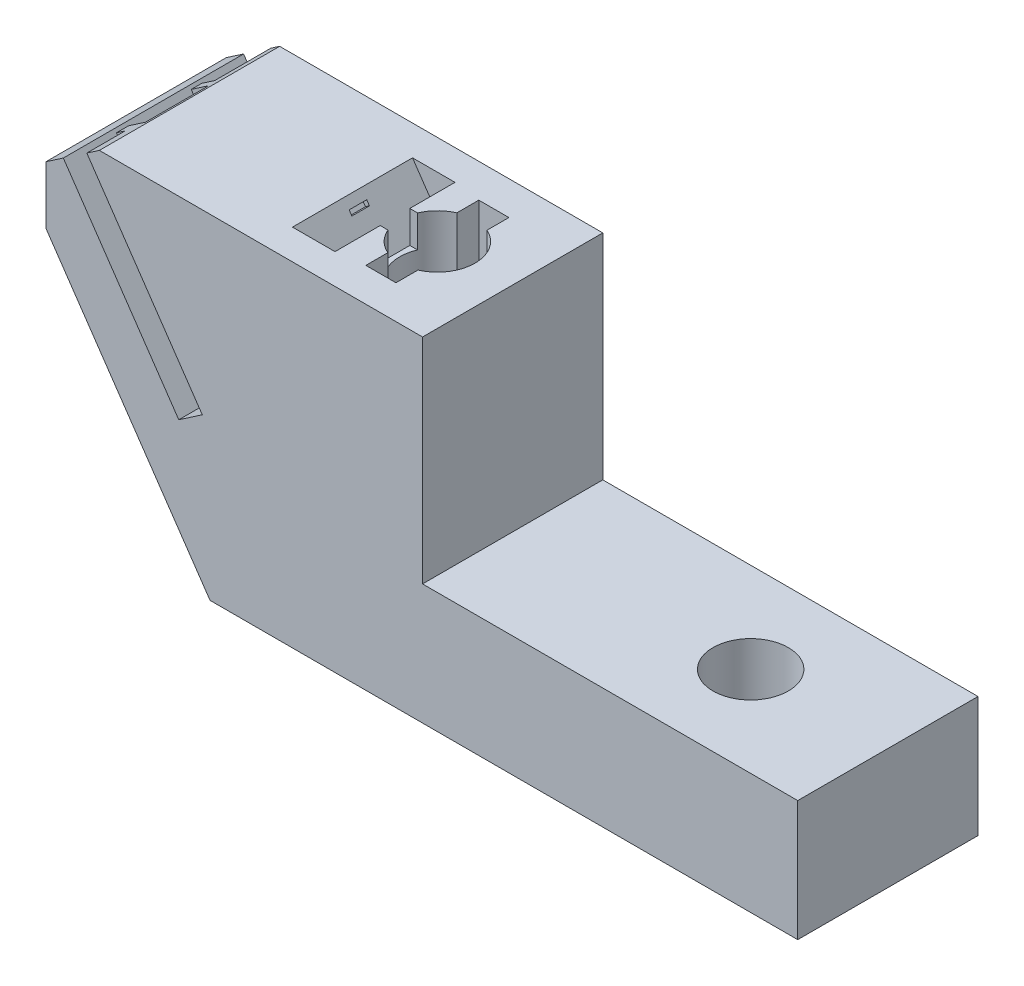
SolidWorks part; units mm, degrees
ref_plane "Front Plane" through (0, 0, 0) normal (0, 0, 1) x (1, 0, 0)
ref_plane "Top Plane" through (0, 0, 0) normal (0, 1, 0) x (1, 0, 0)
ref_plane "Right Plane" through (0, 0, 0) normal (1, 0, 0) x (0, 0, -1)
sketch "Sketch1" plane through (0, 0, 0) normal (0, 0, 1) x (1, 0, 0)
  line L6 (2.54, 23.749) -> (2.54, 14.224) construction
  line L7 (0, 0) -> (5.08, 0)
  line L8 (0, 0) -> (0, 14.224)
  line L9 (0, 14.224) -> (5.08, 14.224)
  line L14 (5.08, 0) -> (5.08, 14.224)
  line L19 (-4.6156, 24.384) -> (-4.0424, 23.5451)
  line L29 (-11.679, 6.821) -> (-21.27, 20.8572)
  line L31 (-22.86, -3.81) -> (8.89, -3.81)
  line L33 (-3.4692, 22.7063) -> (-1.0331, 19.1411)
  line L34 (-21.27, 20.8572) -> (-22.86, 19.7707)
  line L35 (-4.0424, 23.5451) -> (-3.4692, 22.7063)
  line L36 (-28.3165, 23.749) -> (25.4257, 23.749)
  line L37 (-28.3165, 23.749) -> (-28.3165, 38.989)
  line L38 (-28.3165, 38.989) -> (25.4257, 38.989)
  line L39 (25.4257, 23.749) -> (25.4257, 38.989)
  line L40 (2.54, 38.989) -> (2.54, 23.749) construction
  line L41 (2.54, 31.369) -> (-11.8891, 14.2184) construction
  line L42 (-21.27, 20.8572) -> (-17.9673, 23.1139)
  line L43 (-11.679, 6.821) -> (-8.3764, 9.0777)
  line L44 (-8.3764, 9.0777) -> (-9.5047, 10.729)
  line L45 (-1.0331, 19.1411) -> (0, 19.1411)
  line L46 (-17.9673, 23.1139) -> (-16.1085, 24.384)
  line L47 (-16.1085, 24.384) -> (-4.6156, 24.384)
  line L48 (0, 19.1411) -> (0, 14.224)
  line L49 (-4.329, 23.9646) -> (-17.443, 23.4721)
  line L50 (-4.329, 23.9646) -> (-3.7558, 23.1257)
  line L51 (-3.7558, 23.1257) -> (-8.3764, 9.0777)
  line L52 (-8.8063, 9.7068) -> (2.54, 42.6656) construction
  line L53 (2.54, 38.989) -> (2.54, 42.6656) construction
  line L54 (8.89, -3.81) -> (8.89, 24.384)
  line L55 (8.89, 24.384) -> (5.08, 24.384)
  line L56 (5.08, 14.224) -> (5.08, 24.384)
  line L57 (2.54, 23.749) -> (-4.0424, 23.5451) construction
  line L58 (2.54, 38.989) -> (-4.0424, 23.5451) construction
  line L59 (-4.0424, 23.5451) -> (-9.5047, 10.729) construction
  line L60 (-4.0424, 23.5451) -> (-17.9673, 23.1139) construction
  line L61 (-17.9673, 23.1139) -> (-9.5047, 10.729)
  line L62 (-8.8063, 9.7068) -> (-9.8549, 8.9903) construction
  line L63 (-9.8549, 8.9903) -> (-18.2379, 21.2588) construction
  line L64 (-18.2379, 21.2588) -> (-17.1893, 21.9753) construction
  line L69 (-17.1893, 21.9753) -> (2.54, 24.3311) construction
  line L70 (-22.86, 19.7707) -> (-22.86, -3.81)
  dimension "D1" = 5.08
  dimension "D2" = 14.224
  dimension "D3" = 0.635
  dimension "D4" = 10.16
  dimension "D5" = 4
  dimension "D6" = 15.24
  dimension "D7" = 17
  dimension "D8" = 31.75
  dimension "D9" = 1.59
  dimension "D10" = 1.016
  dimension "D11" = 6.35
  dimension "D12" = 3.81
  dimension "D13" = 3.81
  dimension "D14" = 0.635
  dimension "D15" = 0.508
  dimension "D16" = 0.508
  dimension "D17" = 0.762
  dimension "D18" = 14.859
  dimension "D19" = 1.27
  dimension "D20" = 15
extrude "Boss-Extrude1" add sketch "Sketch1" along normal blind 2.5 contours L34 L70 L31 L54 L36 L56 L14 L7 L8 L48 L45 L33 L35 L19 L46 L61 L44 L43 L29 | L47 L46 L36 L19 | L56 L36 L54 L55
sketch "Sketch2" plane through (0, 0, 2.5) normal (0, 0, 1) x (1, 0, 0)
  line L0 (-21.27, 20.8572) -> (-11.679, 6.821)
  line L1 (-21.27, 20.8572) -> (-18.0093, 23.0852)
  line L2 (-11.679, 6.821) -> (-8.4184, 9.049)
  line L3 (-18.0093, 23.0852) -> (-8.4184, 9.049)
  line L4 (-18.0093, 23.0852) -> (-16.1085, 24.384)
  line L5 (-16.1085, 24.384) -> (8.89, 24.384)
  line L6 (8.89, 24.384) -> (8.89, -3.81)
  line L7 (8.89, -3.81) -> (-22.86, -3.81)
  line L8 (-22.86, -3.81) -> (-22.86, 19.7707)
  line L9 (-22.86, 19.7707) -> (-21.27, 20.8572)
  line M1 (-21.27, 20.8572) -> (-22.86, 19.7707)
  line M2 (-22.86, 19.7707) -> (-22.86, -3.81)
  line M3 (-22.86, -3.81) -> (8.89, -3.81)
  line M4 (8.89, -3.81) -> (8.89, 24.384)
  line M5 (8.89, 24.384) -> (5.08, 24.384)
  line M6 (5.08, 24.384) -> (5.08, 0)
  line M7 (5.08, 0) -> (0, 0)
  line M8 (0, 0) -> (0, 19.1411)
  line M9 (0, 19.1411) -> (-1.0331, 19.1411)
  line M10 (-1.0331, 19.1411) -> (-3.7558, 23.1257)
  line M11 (-3.7558, 23.1257) -> (-8.3764, 9.0777)
  line M12 (-8.3764, 9.0777) -> (-11.679, 6.821)
  line M13 (-11.679, 6.821) -> (-21.27, 20.8572)
extrude "Boss-Extrude2" add sketch "Sketch2" along normal blind 6.35 contours M13 M1 M2 M3 M4 M5 M6 M7 M8 M9 M10 M11 M12 | L5 L4 L3 M12 M11 M10 M9 M8 M7 M6
sketch "Sketch3" plane through (0, 0, 0) normal (0, 0, -1) x (-1, 0, 0)
  line L0 (-8.89, 24.384) -> (-8.89, -3.81)
  line L1 (-8.89, -3.81) -> (22.86, -3.81)
  line L2 (22.86, -3.81) -> (22.86, 19.7707)
  line L3 (22.86, 19.7707) -> (21.27, 20.8572)
  line L4 (21.27, 20.8572) -> (11.679, 6.821)
  line L5 (11.679, 6.821) -> (8.3764, 9.0777)
  line L6 (8.3764, 9.0777) -> (18.0093, 23.0852)
  line L7 (18.0093, 23.0852) -> (16.1085, 24.384)
  line L8 (16.1085, 24.384) -> (-8.89, 24.384)
extrude "Boss-Extrude3" add sketch "Sketch3" along normal blind 6.35
sketch "Sketch4" plane through (0, 24.384, 0) normal (0, 1, 0) x (1, 0, 0)
  line L0 (2.54, 0) -> (2.54, -2.5) construction
  line L1 (-4.6156, 0) -> (5.08, 0) construction
  line L2 (5.08, -2.5) -> (-4.6156, -2.5) construction
  line L3 (-22.86, 0) -> (8.89, 0) construction
  line L4 (5.08, -2.5) -> (5.08, 0) construction
  circle A0 centre (2.54, -1.25) radius 3.175
  dimension "D2" = 6.35
  dimension "D1" = 2.54
extrude "Cut-Extrude1" cut sketch "Sketch4" against normal blind 25.4
sketch "Sketch5" plane through (0, -1.016, 0) normal (0, 1, 0) x (1, 0, 0)
  circle A0 centre (2.54, -1.25) radius 1.5875
  circle A1 centre (2.54, -1.25) radius 3.175
  circle A2 centre (2.54, -1.25) radius 3.175 construction
  dimension "D2" = 3.175
  dimension "D1" = 0
extrude "Cut-Extrude2" cut sketch "Sketch5" against normal blind 25.4
sketch "Sketch6" plane through (0, 0, 8.85) normal (0, 0, 1) x (1, 0, 0)
  line L0 (-22.86, 16.4309) -> (-9.0294, -3.81)
  line L1 (-22.86, 19.7707) -> (-22.86, -3.81) construction
  line L2 (-22.86, -3.81) -> (8.89, -3.81) construction
  line L3 (-11.679, 6.821) -> (-21.27, 20.8572) construction
  line L4 (-22.86, 16.4309) -> (-22.86, -3.81)
  line L5 (-22.86, -3.81) -> (-9.0294, -3.81)
  dimension "D1" = 3.81
extrude "Cut-Extrude3" cut sketch "Sketch6" against normal blind 25.4
sketch "Sketch7" plane through (8.89, 0, 0) normal (1, 0, 0) x (0, 0, -1)
  line L0 (1.925, -1.016) -> (-4.425, -1.016) construction
  line L1 (1.925, -1.016) -> (-4.425, -1.016)
  line L2 (-8.85, 2.159) -> (6.35, 2.159) construction
  line L3 (-8.85, -3.81) -> (-8.85, 24.384) construction
  line L4 (6.35, 24.384) -> (6.35, -3.81) construction
  circle A0 centre (-1.25, 2.159) radius 3.175
  dimension "D1" = 6.35
extrude "Cut-Extrude4" cut sketch "Sketch7" against normal up to next contours L2 A0 | A0 L2
sketch "Sketch8" plane through (0, 24.384, 0) normal (0, 1, 0) x (1, 0, 0)
  line L1 (1.27, -6.0125) -> (3.81, -6.0125)
  line L2 (1.27, -6.0125) -> (1.27, 3.5125)
  line L3 (1.27, 3.5125) -> (3.81, 3.5125)
  line L4 (3.81, -6.0125) -> (3.81, 3.5125)
  line L5 (1.27, -6.0125) -> (3.81, 3.5125) construction
  line L6 (1.27, 3.5125) -> (3.81, -6.0125) construction
  point P0 (2.54, -1.25)
  dimension "D1" = 9.525
  dimension "D2" = 2.54
extrude "Cut-Extrude5" cut sketch "Sketch8" against normal up to surface (25.4 mm away) up to face at (2.54, -1.016, 2.8375)
sketch "Sketch9" plane through (-6.8946, 10.0902, 0) normal (-0.5642, 0.8257, 0) x (0.8257, 0.5642, 0)
  line L1 (-1.8455, -4.6028) -> (-3.5726, -4.6028)
  line L2 (-3.5726, -4.6028) -> (-3.5726, -5.6188)
  line L3 (-3.5726, -5.6188) -> (-2.6836, -5.6188)
  line L4 (-2.6836, -5.6188) -> (-2.6836, -8.85)
  line L5 (-1.8455, -8.85) -> (-5.7946, -8.85) construction
  line L6 (-2.6836, -8.85) -> (-1.8455, -8.85)
  line L9 (-1.7946, 6.35) -> (-1.7946, 0) construction
  line L10 (-3.6235, 0.7312) -> (-3.6235, 1.6202)
  line L11 (-1.7946, 0.7312) -> (-3.6235, 0.7312)
  line L12 (-2.7091, 0.7312) -> (-2.7091, -4.6028) construction
  line L13 (-5.7946, 6.35) -> (-5.0834, 6.35)
  line L14 (-5.7946, 6.35) -> (-5.7946, -8.85)
  line L15 (-5.7946, -8.85) -> (-5.0834, -8.85)
  line L16 (-5.0834, 6.35) -> (-5.0834, -8.85)
  line L17 (-0.6688, -2.5) -> (-0.6688, 0) construction
  line L18 (-1.8455, -8.85) -> (-1.8455, -2.5) construction
  line L19 (-3.6235, 1.6202) -> (-2.3026, 1.6202)
  line L20 (-2.3026, 1.6202) -> (-2.3026, 6.35)
  line L21 (-5.7946, 6.35) -> (-1.7946, 6.35) construction
  line L23 (-1.7946, -2.5) -> (-1.7946, 0) construction
  line L24 (-1.7946, 0.7312) -> (-1.7946, 6.35)
  line L27 (-1.8455, 6.35) -> (0.4567, 6.35) construction
  line L28 (-2.3026, 6.35) -> (-1.7946, 6.35)
  point P28 (-0.6688, -1.25)
  line M15 (-1.7946, 0) -> (-1.7946, 6.35)
  line M16 (-1.7946, 6.35) -> (-5.7946, 6.35)
  line M17 (-5.7946, 6.35) -> (-5.7946, -8.85)
  line M18 (-5.7946, -8.85) -> (-1.8455, -8.85)
  line M19 (-1.8455, -8.85) -> (-1.8455, -2.5)
  dimension "D1" = 0.7112
  dimension "D2" = 5.334
  dimension "D3" = 1.9812
  dimension "D4" = 0.508
  dimension "D5" = 0.889
  dimension "D6" = 0.889
  dimension "D7" = 1.016
  dimension "D8" = 1.778
extrude "Boss-Extrude4" add sketch "Sketch9" along normal up to surface (17 mm away) contours L16 M16 M17 M18 | L20 L19 L10 L11 M15 M16 | L3 L4 L1 L2 M18 M19 up to face at (-17.2912, 23.5758, 1.25)
sketch "Sketch10" plane through (-6.8946, 10.0902, 0) normal (-0.5642, 0.8257, 0) x (0.8257, 0.5642, 0)
  line L15 (-5.0834, -8.85) -> (-2.6836, -8.85)
  line L16 (-2.6836, -8.85) -> (-2.6836, -5.6188)
  line L17 (-2.6836, -5.6188) -> (-3.5726, -5.6188)
  line L18 (-3.5726, -5.6188) -> (-3.5726, -4.6028)
  line L19 (-3.5726, -4.6028) -> (-1.8455, -4.6028)
  line L20 (-1.8455, -4.6028) -> (-1.8455, -2.5)
  line L21 (-1.8455, -2.5) -> (-1.7946, -2.5)
  line L22 (-1.7946, -2.5) -> (-1.7946, 0)
  line L23 (-1.7946, 0) -> (-1.7946, 0.7312)
  line L24 (-1.7946, 0.7312) -> (-3.6235, 0.7312)
  line L25 (-3.6235, 0.7312) -> (-3.6235, 1.6202)
  line L26 (-3.6235, 1.6202) -> (-2.3026, 1.6202)
  line L27 (-2.3026, 1.6202) -> (-2.3026, 6.35)
  line L28 (-2.3026, 6.35) -> (-5.0834, 6.35)
  line L29 (-5.0834, 6.35) -> (-5.0834, -8.85)
  line L30 (-5.0834, -8.85) -> (-2.6836, -8.85)
  line L31 (-2.6836, -8.85) -> (-2.6836, -5.6188)
  line L32 (-2.6836, -5.6188) -> (-3.5726, -5.6188)
  line L33 (-3.5726, -5.6188) -> (-3.5726, -4.6028)
  line L34 (-3.5726, -4.6028) -> (-1.8455, -4.6028)
  line L35 (-1.8455, -4.6028) -> (-1.8455, -2.5)
  line L36 (-1.8455, -2.5) -> (-1.7946, -2.5)
  line L37 (-1.7946, -2.5) -> (-1.7946, 0)
  line L38 (-1.7946, 0) -> (-1.7946, 0.7312)
  line L39 (-1.7946, 0.7312) -> (-3.6235, 0.7312)
  line L40 (-3.6235, 0.7312) -> (-3.6235, 1.6202)
  line L41 (-3.6235, 1.6202) -> (-2.3026, 1.6202)
  line L42 (-2.3026, 1.6202) -> (-2.3026, 6.35)
  line L43 (-2.3026, 6.35) -> (-5.0834, 6.35)
  line L44 (-5.0834, 6.35) -> (-5.0834, -8.85)
  dimension "D1" = 0
extrude "Boss-Extrude5" add sketch "Sketch10" along normal blind 1.016
sketch "Sketch11" plane through (-16.4856, 24.1263, 0) normal (-0.5642, 0.8257, 0) x (0.8257, 0.5642, 0)
  line L0 (-7.7204, -8.85) -> (-5.0834, -8.85) construction
  line L1 (-5.0834, -8.85) -> (-5.0834, 6.35) construction
  line L2 (-5.0834, 6.35) -> (-7.7204, 6.35) construction
  line L3 (-7.7204, 6.35) -> (-7.7204, -8.85) construction
  line L4 (-3.6235, 0.7312) -> (-1.8455, 0.7312) construction
  line L5 (-1.8455, 0.7312) -> (-1.8455, 0) construction
  line L6 (-1.8455, 0) -> (-0.6688, 0) construction
  line L7 (-0.6688, 0) -> (-0.6688, -2.5) construction
  line L8 (-0.6688, -2.5) -> (-1.8455, -2.5) construction
  line L9 (-1.8455, -2.5) -> (-1.8455, -4.6028) construction
  line L10 (-1.8455, -4.6028) -> (-3.5726, -4.6028) construction
  line L11 (-3.5726, -4.6028) -> (-3.5726, -5.6188) construction
  line L12 (-3.5726, -5.6188) -> (-2.6836, -5.6188) construction
  line L13 (-2.6836, -5.6188) -> (-2.6836, -8.85) construction
  line L14 (-2.6836, -8.85) -> (0.4567, -8.85) construction
  line L15 (0.4567, -8.85) -> (0.4567, 6.35) construction
  line L16 (0.4567, 6.35) -> (-2.3026, 6.35) construction
  line L17 (-2.3026, 6.35) -> (-2.3026, 1.6202) construction
  line L18 (-2.3026, 1.6202) -> (-3.6235, 1.6202) construction
  line L19 (-3.6235, 1.6202) -> (-3.6235, 0.7312) construction
  line L20 (-7.7204, -8.85) -> (-5.0834, -8.85)
  line L21 (-5.0834, -8.85) -> (-5.0834, 6.35)
  line L22 (-5.0834, 6.35) -> (-7.7204, 6.35)
  line L23 (-7.7204, 6.35) -> (-7.7204, -8.85)
  line L24 (-3.6235, 0.7312) -> (-1.8455, 0.7312)
  line L25 (-1.8455, 0.7312) -> (-1.8455, 0)
  line L26 (-1.8455, 0) -> (-0.6688, 0)
  line L27 (-0.6688, 0) -> (-0.6688, -2.5)
  line L28 (-0.6688, -2.5) -> (-1.8455, -2.5)
  line L29 (-1.8455, -2.5) -> (-1.8455, -4.6028)
  line L30 (-1.8455, -4.6028) -> (-3.5726, -4.6028)
  line L31 (-3.5726, -4.6028) -> (-3.5726, -5.6188)
  line L32 (-3.5726, -5.6188) -> (-2.6836, -5.6188)
  line L33 (-2.6836, -5.6188) -> (-2.6836, -8.85)
  line L34 (-2.6836, -8.85) -> (0.4567, -8.85)
  line L35 (0.4567, -8.85) -> (0.4567, 6.35)
  line L36 (0.4567, 6.35) -> (-2.3026, 6.35)
  line L37 (-2.3026, 6.35) -> (-2.3026, 1.6202)
  line L38 (-2.3026, 1.6202) -> (-3.6235, 1.6202)
  line L39 (-3.6235, 1.6202) -> (-3.6235, 0.7312)
  line L41 (-1.8455, 0) -> (-0.6688, 0)
  line L42 (-1.8455, 0) -> (-1.8455, -2.5)
  line L43 (-1.8455, -2.5) -> (-0.6688, -2.5)
  line L44 (-0.6688, 0) -> (-0.6688, -2.5)
  line M25 (-3.6235, 0.7312) -> (-1.8455, 0.7312)
  line M26 (-1.8455, 0.7312) -> (-1.8455, 0)
  line M27 (-1.8455, 0) -> (-0.6688, 0)
  line M28 (-0.6688, 0) -> (-0.6688, -2.5)
  line M29 (-0.6688, -2.5) -> (-1.8455, -2.5)
  line M30 (-1.8455, -2.5) -> (-1.8455, -4.6028)
  line M31 (-1.8455, -4.6028) -> (-3.5726, -4.6028)
  line M32 (-3.5726, -4.6028) -> (-3.5726, -5.6188)
  line M33 (-3.5726, -5.6188) -> (-2.6836, -5.6188)
  line M34 (-2.6836, -5.6188) -> (-2.6836, -8.85)
  line M35 (-2.6836, -8.85) -> (0.4567, -8.85)
  line M36 (0.4567, -8.85) -> (0.4567, 6.35)
  line M37 (0.4567, 6.35) -> (-2.3026, 6.35)
  line M38 (-2.3026, 6.35) -> (-2.3026, 1.6202)
  line M39 (-2.3026, 1.6202) -> (-3.6235, 1.6202)
  line M40 (-3.6235, 1.6202) -> (-3.6235, 0.7312)
extrude "Boss-Extrude6" add sketch "Sketch11" along normal blind 1.27 contours L42 M27 M29 M28 | M40 M25 M26 M27 M28 M29 M30 M31 M32 M33 M34 M35 M36 M37 M38 M39 | L22 L23 L20 L21
sketch "Sketch12" plane through (0, 0, 8.85) normal (0, 0, 1) x (1, 0, 0)
  line L0 (-16.1085, 24.384) -> (-18.3596, 24.384)
  line L1 (-19.4178, 23.6609) -> (-16.825, 25.4326) construction
  line L2 (-18.3596, 24.384) -> (-16.825, 25.4326)
  line L3 (-16.825, 25.4326) -> (-16.1085, 24.384)
  line L4 (-22.86, 19.7707) -> (-22.86, 21.3089)
  line L5 (-23.5765, 20.8193) -> (-21.3993, 22.307) construction
  line L6 (-22.86, 21.3089) -> (-23.5765, 20.8193)
  line L7 (-23.5765, 20.8193) -> (-22.86, 19.7707)
extrude "Cut-Extrude6" cut sketch "Sketch12" against normal through all
sketch "Sketch13" plane through (0, 19.1411, 0) normal (0, 1, 0) x (1, 0, 0)
  line L3 (-0.3786, 0) -> (-1.0331, 0)
  line L4 (-1.0331, 0) -> (-1.0331, -2.5)
  line L5 (-1.0331, -2.5) -> (-0.3786, -2.5)
  line L6 (-0.3786, 0) -> (-1.0331, 0)
  line L7 (-1.0331, 0) -> (-1.0331, -2.5)
  line L8 (-1.0331, -2.5) -> (-0.3786, -2.5)
  arc A1 (-0.3786, 0) -> (-0.3786, -2.5) centre (2.54, -1.25) ccw
  arc A2 (-0.3786, 0) -> (-0.3786, -2.5) centre (2.54, -1.25) ccw
  dimension "D1" = 0
extrude "Boss-Extrude7" add sketch "Sketch13" along normal blind 2.54
sketch "Sketch14" plane through (8.2119, 5.6112, 0) normal (0.8257, 0.5642, 0) x (0, 0, -1)
  line L0 (0, 22.2288) -> (0, 22.7368) construction
  line L1 (0, 22.7368) -> (-2.5, 22.7368) construction
  line L2 (-2.5, 22.7368) -> (-2.5, 22.2288) construction
  line L3 (-2.5, 22.2288) -> (0, 22.2288) construction
  line L4 (0, 16.3868) -> (0, 21.2128) construction
  line L5 (0, 21.2128) -> (-2.5, 21.2128) construction
  line L6 (-2.5, 21.2128) -> (-2.5, 16.3868) construction
  line L7 (-2.5, 16.3868) -> (0, 16.3868) construction
  line L8 (0, 22.2288) -> (0, 22.7368)
  line L9 (0, 22.7368) -> (-2.5, 22.7368)
  line L10 (-2.5, 22.7368) -> (-2.5, 22.2288)
  line L11 (-2.5, 22.2288) -> (0, 22.2288)
  line L12 (0, 16.3868) -> (0, 21.2128)
  line L13 (0, 21.2128) -> (-2.5, 21.2128)
  line L14 (-2.5, 21.2128) -> (-2.5, 16.3868)
  line L15 (-2.5, 16.3868) -> (0, 16.3868)
  dimension "D1" = 2.5
sketch "Sketch15" plane through (0, 0, 0) normal (0, 0, 1) x (1, 0, 0)
  line L0 (-4.329, 23.9646) -> (-3.7558, 23.1257)
  line L1 (-4.329, 23.9646) -> (-4.6156, 24.384) construction
  line L2 (-3.7558, 23.1257) -> (-1.0331, 19.1411) construction
  line L3 (-4.2633, 23.1481) -> (-3.9277, 23.3774)
  line L4 (-4.4925, 23.4836) -> (-4.8089, 23.9465)
  line L5 (-4.8089, 23.9465) -> (-4.329, 23.9646)
  line L6 (-4.4925, 23.4836) -> (-4.157, 23.7129)
  line L7 (-4.2633, 23.1481) -> (-3.9157, 22.6394)
  line L8 (-3.9157, 22.6394) -> (-3.7558, 23.1257)
  line L9 (-4.0424, 23.5451) -> (-3.9209, 23.3673) construction
  line L10 (-4.0424, 23.5451) -> (-4.1638, 23.7229) construction
  line L11 (-1.0331, 19.1411) -> (-3.7558, 23.1257) construction
  line L25 (-1.0331, 19.1411) -> (-1.0331, 21.6811)
  line L26 (-1.0331, 21.6811) -> (-0.3786, 21.6811)
  line L27 (-0.3786, 21.6811) -> (-0.3786, 24.384)
  line L28 (-0.3786, 24.384) -> (-4.6156, 24.384)
  line L29 (-4.6156, 24.384) -> (-4.329, 23.9646)
  line L30 (-4.329, 23.9646) -> (-10.0694, 23.749)
  line L31 (-10.0694, 23.749) -> (-17.0378, 23.749)
  line L32 (-17.0378, 23.749) -> (-18.0093, 23.0852)
  line L33 (-18.0093, 23.0852) -> (-8.9521, 9.9148)
  line L34 (-8.9521, 9.9148) -> (-8.9496, 9.9166)
  line L35 (-8.9496, 9.9166) -> (-8.3764, 9.0777)
  line L36 (-8.3764, 9.0777) -> (-3.7558, 23.1257)
  line L37 (-3.7558, 23.1257) -> (-1.0331, 19.1411)
  line L38 (-1.0331, 19.1411) -> (-1.0331, 21.6811)
  line L39 (-1.0331, 21.6811) -> (-0.3786, 21.6811)
  line L40 (-0.3786, 21.6811) -> (-0.3786, 24.384)
  line L41 (-0.3786, 24.384) -> (-4.6156, 24.384)
  line L42 (-4.6156, 24.384) -> (-4.329, 23.9646)
  line L43 (-4.329, 23.9646) -> (-10.0694, 23.749)
  line L44 (-10.0694, 23.749) -> (-17.0378, 23.749)
  line L45 (-17.0378, 23.749) -> (-18.0093, 23.0852)
  line L46 (-18.0093, 23.0852) -> (-8.9521, 9.9148)
  line L47 (-8.9521, 9.9148) -> (-8.9496, 9.9166)
  line L48 (-8.9496, 9.9166) -> (-8.3764, 9.0777)
  line L49 (-8.3764, 9.0777) -> (-3.7558, 23.1257)
  line L50 (-3.7558, 23.1257) -> (-1.0331, 19.1411)
  line M26 (-4.329, 23.9646) -> (-10.0694, 23.749)
  line M32 (-8.3764, 9.0777) -> (-3.7558, 23.1257)
  dimension "D1" = 0.4064
  dimension "D2" = 0.4064
  dimension "D3" = 0
  dimension "D4" = 0.2032
extrude "Boss-Extrude8" add sketch "Sketch15" along normal blind 2.54 contours L4 L6 L0 M26 | L3 L7 L0 M32
sketch "Sketch16" plane through (0, 0, 0) normal (0, 0, 1) x (1, 0, 0)
  line L0 (-4.157, 23.7129) -> (-3.9277, 23.3774)
  line L1 (-4.2633, 23.1481) -> (-3.9277, 23.3774)
  line L2 (-4.2633, 23.1481) -> (-4.4925, 23.4836)
  line L3 (-4.4925, 23.4836) -> (-4.157, 23.7129)
  line L17 (-3.9157, 22.6394) -> (-4.2633, 23.1481)
  line L18 (-4.2633, 23.1481) -> (-3.9277, 23.3774)
  line L19 (-3.9277, 23.3774) -> (-1.0331, 19.1411)
  line L20 (-1.0331, 19.1411) -> (-1.0331, 21.6811)
  line L21 (-1.0331, 21.6811) -> (-0.3786, 21.6811)
  line L22 (-0.3786, 21.6811) -> (-0.3786, 24.384)
  line L23 (-0.3786, 24.384) -> (-4.6156, 24.384)
  line L24 (-4.6156, 24.384) -> (-4.157, 23.7129)
  line L25 (-4.157, 23.7129) -> (-4.4925, 23.4836)
  line L26 (-4.4925, 23.4836) -> (-4.8089, 23.9465)
  line L27 (-4.8089, 23.9465) -> (-10.0694, 23.749)
  line L28 (-10.0694, 23.749) -> (-17.0378, 23.749)
  line L29 (-17.0378, 23.749) -> (-18.0093, 23.0852)
  line L30 (-18.0093, 23.0852) -> (-8.9521, 9.9148)
  line L31 (-8.9521, 9.9148) -> (-8.9496, 9.9166)
  line L32 (-8.9496, 9.9166) -> (-8.3764, 9.0777)
  line L33 (-8.3764, 9.0777) -> (-3.9157, 22.6394)
  line L34 (-3.9157, 22.6394) -> (-4.2633, 23.1481)
  line L35 (-4.2633, 23.1481) -> (-3.9277, 23.3774)
  line L36 (-3.9277, 23.3774) -> (-1.0331, 19.1411)
  line L37 (-1.0331, 19.1411) -> (-1.0331, 21.6811)
  line L38 (-1.0331, 21.6811) -> (-0.3786, 21.6811)
  line L39 (-0.3786, 21.6811) -> (-0.3786, 24.384)
  line L40 (-0.3786, 24.384) -> (-4.6156, 24.384)
  line L41 (-4.6156, 24.384) -> (-4.157, 23.7129)
  line L42 (-4.157, 23.7129) -> (-4.4925, 23.4836)
  line L43 (-4.4925, 23.4836) -> (-4.8089, 23.9465)
  line L44 (-4.8089, 23.9465) -> (-10.0694, 23.749)
  line L45 (-10.0694, 23.749) -> (-17.0378, 23.749)
  line L46 (-17.0378, 23.749) -> (-18.0093, 23.0852)
  line L47 (-18.0093, 23.0852) -> (-8.9521, 9.9148)
  line L48 (-8.9521, 9.9148) -> (-8.9496, 9.9166)
  line L49 (-8.9496, 9.9166) -> (-8.3764, 9.0777)
  line L50 (-8.3764, 9.0777) -> (-3.9157, 22.6394)
  line M19 (-4.2633, 23.1481) -> (-3.9277, 23.3774)
  line M26 (-4.157, 23.7129) -> (-4.4925, 23.4836)
  dimension "D1" = 0
extrude "Boss-Extrude9" add sketch "Sketch16" along normal blind 0.508 contours L2 L0 M19 M26
sketch "Sketch17" plane through (0, 0, 2.5) normal (0, 0, -1) x (-1, 0, 0)
  line L0 (4.157, 23.7129) -> (3.9277, 23.3774)
  line L1 (3.9277, 23.3774) -> (4.2633, 23.1481)
  line L2 (4.2633, 23.1481) -> (4.4925, 23.4836)
  line L3 (4.4925, 23.4836) -> (4.157, 23.7129)
  line L17 (4.2633, 23.1481) -> (3.9157, 22.6394)
  line L18 (3.9157, 22.6394) -> (8.3764, 9.0777)
  line L19 (8.3764, 9.0777) -> (8.9496, 9.9166)
  line L20 (8.9496, 9.9166) -> (8.9916, 9.8879)
  line L21 (8.9916, 9.8879) -> (18.0093, 23.0852)
  line L22 (18.0093, 23.0852) -> (17.0378, 23.749)
  line L23 (17.0378, 23.749) -> (10.0694, 23.749)
  line L24 (10.0694, 23.749) -> (4.8089, 23.9465)
  line L25 (4.8089, 23.9465) -> (4.4925, 23.4836)
  line L26 (4.4925, 23.4836) -> (4.157, 23.7129)
  line L27 (4.157, 23.7129) -> (4.6156, 24.384)
  line L28 (4.6156, 24.384) -> (0.3786, 24.384)
  line L29 (0.3786, 24.384) -> (0.3786, 21.6811)
  line L30 (0.3786, 21.6811) -> (1.0331, 21.6811)
  line L31 (1.0331, 21.6811) -> (1.0331, 19.1411)
  line L32 (1.0331, 19.1411) -> (3.9277, 23.3774)
  line L33 (3.9277, 23.3774) -> (4.2633, 23.1481)
  line L34 (4.2633, 23.1481) -> (3.9157, 22.6394)
  line L35 (3.9157, 22.6394) -> (8.3764, 9.0777)
  line L36 (8.3764, 9.0777) -> (8.9496, 9.9166)
  line L37 (8.9496, 9.9166) -> (8.9916, 9.8879)
  line L38 (8.9916, 9.8879) -> (18.0093, 23.0852)
  line L39 (18.0093, 23.0852) -> (17.0378, 23.749)
  line L40 (17.0378, 23.749) -> (10.0694, 23.749)
  line L41 (10.0694, 23.749) -> (4.8089, 23.9465)
  line L42 (4.8089, 23.9465) -> (4.4925, 23.4836)
  line L43 (4.4925, 23.4836) -> (4.157, 23.7129)
  line L44 (4.157, 23.7129) -> (4.6156, 24.384)
  line L45 (4.6156, 24.384) -> (0.3786, 24.384)
  line L46 (0.3786, 24.384) -> (0.3786, 21.6811)
  line L47 (0.3786, 21.6811) -> (1.0331, 21.6811)
  line L48 (1.0331, 21.6811) -> (1.0331, 19.1411)
  line L49 (1.0331, 19.1411) -> (3.9277, 23.3774)
  line L50 (3.9277, 23.3774) -> (4.2633, 23.1481)
  line M27 (4.4925, 23.4836) -> (4.157, 23.7129)
  line M34 (3.9277, 23.3774) -> (4.2633, 23.1481)
  dimension "D1" = 0
extrude "Boss-Extrude10" add sketch "Sketch17" along normal blind 0.508 contours L2 L0 M34 M27
sketch "Sketch18" plane through (0, 0, 2.5) normal (0, 0, -1) x (-1, 0, 0)
  line L0 (1.0331, 21.6811) -> (1.0331, 24.384)
  line L5 (1.0331, 19.1411) -> (4.6156, 24.384)
  line L6 (4.6156, 24.384) -> (0.3786, 24.384)
  line L7 (0.3786, 24.384) -> (0.3786, 21.6811)
  line L8 (0.3786, 21.6811) -> (1.0331, 21.6811)
  line L9 (1.0331, 21.6811) -> (1.0331, 19.1411)
  line L10 (1.0331, 19.1411) -> (4.6156, 24.384)
  line L11 (4.6156, 24.384) -> (0.3786, 24.384)
  line L12 (0.3786, 24.384) -> (0.3786, 21.6811)
  line L13 (0.3786, 21.6811) -> (1.0331, 21.6811)
  line L14 (1.0331, 21.6811) -> (1.0331, 19.1411)
  line M6 (1.0331, 19.1411) -> (4.6156, 24.384)
  line M7 (4.6156, 24.384) -> (0.3786, 24.384)
  line M10 (1.0331, 21.6811) -> (1.0331, 19.1411)
  dimension "D1" = 0
extrude "Cut-Extrude7" cut sketch "Sketch18" against normal blind 3.81 contours L0 M10 M6 M7
sketch "Sketch19" plane through (0, 0, 0) normal (0, 0, 1) x (1, 0, 0)
  line L0 (-1.0331, 21.6811) -> (-1.0331, 24.384)
  line L5 (-0.3786, 24.384) -> (-4.6156, 24.384)
  line L6 (-4.6156, 24.384) -> (-1.0331, 19.1411)
  line L7 (-1.0331, 19.1411) -> (-1.0331, 21.6811)
  line L8 (-1.0331, 21.6811) -> (-0.3786, 21.6811)
  line L9 (-0.3786, 21.6811) -> (-0.3786, 24.384)
  line L10 (-0.3786, 24.384) -> (-4.6156, 24.384)
  line L11 (-4.6156, 24.384) -> (-1.0331, 19.1411)
  line L12 (-1.0331, 19.1411) -> (-1.0331, 21.6811)
  line L13 (-1.0331, 21.6811) -> (-0.3786, 21.6811)
  line L14 (-0.3786, 21.6811) -> (-0.3786, 24.384)
  line M6 (-0.3786, 24.384) -> (-4.6156, 24.384)
  line M7 (-4.6156, 24.384) -> (-1.0331, 19.1411)
  line M8 (-1.0331, 19.1411) -> (-1.0331, 21.6811)
  dimension "D1" = 0
extrude "Cut-Extrude8" cut sketch "Sketch19" against normal blind 3.81 contours L0 M8 M6 M7
sketch "Sketch20" plane through (0, 0, 0) normal (0, 0, 1) x (1, 0, 0)
  line L0 (-4.4925, 23.4836) -> (-10.0694, 23.749)
  line L8 (-8.3764, 9.0777) -> (-3.9157, 22.6394)
  line L9 (-3.9157, 22.6394) -> (-4.8089, 23.9465)
  line L10 (-4.8089, 23.9465) -> (-10.0694, 23.749)
  line L11 (-10.0694, 23.749) -> (-17.0378, 23.749)
  line L12 (-17.0378, 23.749) -> (-18.0093, 23.0852)
  line L13 (-18.0093, 23.0852) -> (-8.9521, 9.9148)
  line L14 (-8.9521, 9.9148) -> (-8.9496, 9.9166)
  line L15 (-8.9496, 9.9166) -> (-8.3764, 9.0777)
  line L16 (-8.3764, 9.0777) -> (-3.9157, 22.6394)
  line L17 (-3.9157, 22.6394) -> (-4.8089, 23.9465)
  line L18 (-4.8089, 23.9465) -> (-10.0694, 23.749)
  line L19 (-10.0694, 23.749) -> (-17.0378, 23.749)
  line L20 (-17.0378, 23.749) -> (-18.0093, 23.0852)
  line L21 (-18.0093, 23.0852) -> (-8.9521, 9.9148)
  line L22 (-8.9521, 9.9148) -> (-8.9496, 9.9166)
  line L23 (-8.9496, 9.9166) -> (-8.3764, 9.0777)
  line M10 (-3.9157, 22.6394) -> (-4.8089, 23.9465)
  line M11 (-4.8089, 23.9465) -> (-10.0694, 23.749)
  dimension "D1" = 0
extrude "Boss-Extrude11" add sketch "Sketch20" along normal blind 3.81 contours L0 M10 M11
ref_plane "Plane1" through (15.748, 0, 0) normal (1, 0, 0) x (0, 0, -1)
sketch "Sketch21" plane through (0, -3.81, 0) normal (0, -1, 0) x (1, 0, 0)
  line L0 (8.89, -6.35) -> (-9.0294, -6.35) construction
  line L1 (-9.0294, 8.85) -> (40.5254, 8.85)
  line L2 (-9.0294, 8.85) -> (-9.0294, -6.35)
  line L3 (-9.0294, -6.35) -> (40.5254, -6.35)
  line L4 (40.5254, 8.85) -> (40.5254, -6.35)
  line L5 (15.748, 1.25) -> (15.748, 8.85) construction
  line L6 (15.748, 1.25) -> (15.748, -6.35) construction
  line L7 (15.748, 8.85) -> (-9.0294, -6.35) construction
  line L8 (15.748, 8.85) -> (40.5254, -6.35) construction
  line L9 (2.54, 1.25) -> (-9.0294, 1.25) construction
  line L10 (40.5254, 1.25) -> (28.956, 1.25) construction
  circle A0 centre (15.748, 1.25) radius 9.652 construction
  circle A1 centre (2.54, 1.25) radius 1.5875 construction
  circle A2 centre (2.54, 1.25) radius 1.5875 construction
  circle A3 centre (2.54, 1.25) radius 3.175
  circle A5 centre (28.956, 1.25) radius 3.175
  dimension "D1" = 19.304
  dimension "D2" = 6.35
  dimension "D3" = 13.208
  dimension "D4" = 6.35
extrude "Boss-Extrude12" add sketch "Sketch21" against normal blind 10.16
